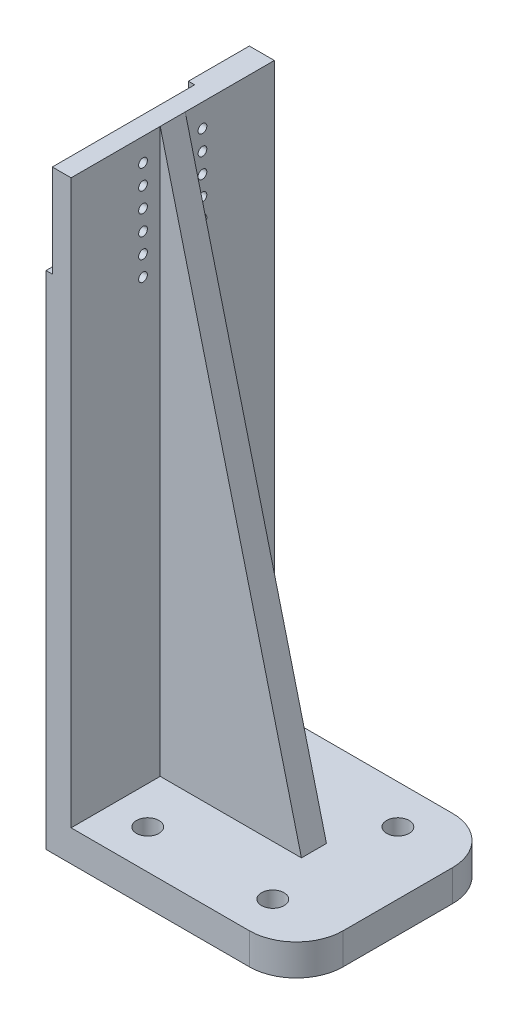
SolidWorks part; units mm, degrees
ref_plane "Ebene vorne" through (0, 0, 0) normal (0, 0, 1) x (1, 0, 0)
ref_plane "Ebene oben" through (0, 0, 0) normal (0, 1, 0) x (1, 0, 0)
ref_plane "Ebene rechts" through (0, 0, 0) normal (1, 0, 0) x (0, 0, -1)
sketch "Skizze1" plane through (0, 0, 0) normal (0, 0, 1) x (1, 0, 0)
  line L0 (-39.374, 163.829) -> (-39.374, -26.171)
  line L1 (-39.374, -26.171) -> (40.626, -26.171)
  line L2 (40.626, -26.171) -> (40.626, -16.171)
  line L3 (40.626, -16.171) -> (-31.374, -16.171)
  line L4 (-31.374, -16.171) -> (-31.374, 163.829)
  line L5 (-39.374, 163.829) -> (-31.374, 163.829)
  dimension "D1" = 80
  dimension "D2" = 8
  dimension "D3" = 10
  dimension "D4" = 190
extrude "Aufsatz-Linear austragen1" add sketch "Skizze1" along normal mid plane 65
sketch "Skizze2" plane through (0, 0, 0) normal (0, 0, 1) x (1, 0, 0)
  line L0 (-31.374, 163.829) -> (13.785, -16.171)
  line L1 (40.626, -16.171) -> (-31.374, -16.171) construction
  line L2 (13.785, -16.171) -> (-31.374, -16.171)
  line L3 (-31.374, -16.171) -> (-31.374, 163.829)
extrude "Aufsatz-Linear austragen2" add sketch "Skizze2" along normal mid plane 8
sketch "Skizze3" plane through (0, -16.171, 0) normal (0, 1, 0) x (1, 0, 0)
  line L9 (-31.374, -32.5) -> (40.626, -32.5)
  line L10 (-31.374, -32.5) -> (-31.374, -52.5)
  line L11 (-31.374, -52.5) -> (40.626, -52.5)
  line L12 (40.626, -32.5) -> (40.626, -52.5)
  circle A1 centre (24.626, -42.5) radius 3.6
  circle A2 centre (-15.374, -42.5) radius 3.6
  dimension "D3" = 72
  dimension "D5" = 20
  dimension "D4" = 7.2
  dimension "D1" = 40
  dimension "D2" = 16
  dimension "D6" = 10
sketch "Skizze4" plane through (-39.374, 0, 0) normal (-1, 0, 0) x (0, 0, 1)
  line L1 (-13, 163.829) -> (13, 163.829)
  line L2 (-13, 163.829) -> (-13, 121.829)
  line L3 (-13, 121.829) -> (13, 121.829)
  line L4 (13, 163.829) -> (13, 121.829)
  line L5 (32.5, 163.829) -> (-32.5, 163.829) construction
  point P6 (0, 163.829)
  point P7 (0, 163.829)
  dimension "D1" = 26
  dimension "D2" = 42
extrude "Schnitt-Linear austragen1" cut sketch "Skizze4" against normal blind 2
sketch "Skizze5" plane through (-37.374, 0, 0) normal (-1, 0, 0) x (0, 0, 1)
  line L0 (-13, 121.829) -> (13, 121.829) construction
  line L1 (-13, 121.829) -> (13, 121.829) construction
  line L2 (-9.5, 124.829) -> (9.5, 124.829) construction
  circle A10 centre (-9.5, 124.829) radius 1.4
  circle A11 centre (9.5, 124.829) radius 1.4
  circle A12 centre (-9.5, 131.159) radius 1.4
  circle A13 centre (9.5, 131.159) radius 1.4
  circle A14 centre (-9.5, 137.489) radius 1.4
  circle A15 centre (9.5, 137.489) radius 1.4
  circle A16 centre (-9.5, 143.819) radius 1.4
  circle A17 centre (9.5, 143.819) radius 1.4
  circle A18 centre (-9.5, 150.149) radius 1.4
  circle A19 centre (9.5, 150.149) radius 1.4
  circle A20 centre (-9.5, 156.479) radius 1.4
  circle A21 centre (9.5, 156.479) radius 1.4
  dimension "D2" = 2.8
  dimension "D1" = 6
  dimension "D3" = 3
  dimension "D4" = 3
extrude "Schnitt-Linear austragen2" cut sketch "Skizze5" against normal blind 10
sketch "Skizze6" plane through (-39.374, 0, 0) normal (-1, 0, 0) x (0, 0, 1)
  line L1 (0, 134.159) -> (34.0283, 134.159)
  line L2 (0, 134.159) -> (0, 164.159)
  line L3 (0, 164.159) -> (34.0283, 164.159)
  line L4 (34.0283, 134.159) -> (34.0283, 164.159)
  circle A0 centre (9.5, 131.159) radius 1.4 construction
  dimension "D1" = 30
  dimension "D2" = 3
extrude "Schnitt-Linear austragen3" cut sketch "Skizze6" against normal blind 2 contours L2 L1 L4 L3
sketch "Skizze7" plane through (0, -16.171, 0) normal (0, 1, 0) x (1, 0, 0)
  line L0 (40.626, -32.5) -> (40.626, 32.5) construction
  line L1 (-39.374, 13) -> (-39.374, 32.5) construction
  line L2 (-31.374, -32.5) -> (-31.374, -4) construction
  circle A0 centre (20.626, 20) radius 3.6
  circle A1 centre (20.626, -20) radius 3.6
  circle A2 centre (-19.374, 20) radius 3.6
  circle A3 centre (-19.374, -20) radius 3.6
  point P8 (40.626, 0)
  dimension "D3" = 20
  dimension "D4" = 7.2
  dimension "D1" = 20
  dimension "D2" = 40
  dimension "D5" = 40
  dimension "D6" = 20
  dimension "D7" = 12
extrude "Schnitt-Linear austragen4" cut sketch "Skizze7" against normal blind 10
fillet "Verrundung1" radius 15 2 edges at (40.626, -21.171, 32.5) (40.626, -21.171, -32.5)
